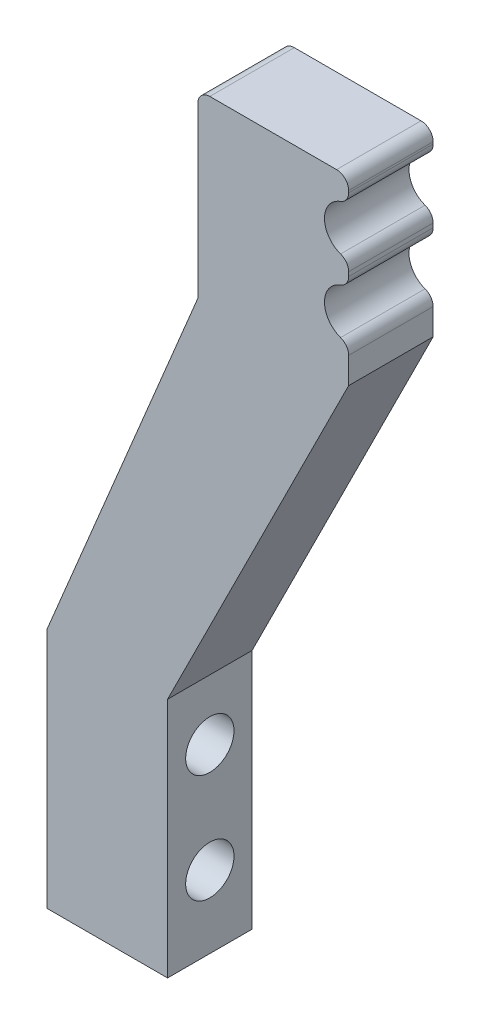
SolidWorks part; units mm, degrees
ref_plane "Front Plane" through (0, 0, 0) normal (0, 0, 1) x (1, 0, 0)
ref_plane "Top Plane" through (0, 0, 0) normal (0, 1, 0) x (1, 0, 0)
ref_plane "Right Plane" through (0, 0, 0) normal (1, 0, 0) x (0, 0, -1)
sketch "Sketch1" plane through (0, 0, 0) normal (0, 0, 1) x (1, 0, 0)
  line L1 (-137.2781, 244.3047) -> (-12.2781, 244.3047)
  line L3 (-262.2781, -205.6953) -> (-12.2781, -205.6953)
  line L4 (-12.2781, 244.3047) -> (-12.2781, -205.6953)
  line L5 (-137.2781, 244.3047) -> (-137.2781, 94.3047)
  line L6 (-137.2781, 94.3047) -> (-262.2781, -205.6953)
extrude "Boss-Extrude2" add sketch "Sketch1" along normal blind 70
sketch "Sketch2" plane through (0, 0, 70) normal (0, 0, 1) x (1, 0, 0)
  line L0 (-262.2781, -205.6953) -> (-262.2781, -405.6953)
  line L2 (-262.2781, -405.6953) -> (-162.2781, -405.6953)
  line L3 (-162.2781, -405.6953) -> (-162.2781, -205.6953)
  line L4 (-262.2781, -205.6953) -> (-12.2781, -205.6953) construction
  line L5 (-162.2781, -205.6953) -> (-262.2781, -205.6953)
extrude "Boss-Extrude3" add sketch "Sketch2" against normal blind 70
sketch "Sketch3" plane through (-162.2781, 0, 0) normal (1, 0, 0) x (0, 0, -1)
  circle A1 centre (-35, -255.6953) radius 20
  circle A2 centre (-35, -345.6953) radius 20
extrude "Cut-Extrude1" cut sketch "Sketch3" against normal blind 132
sketch "Sketch5" plane through (0, 0, 70) normal (0, 0, 1) x (1, 0, 0)
  line L0 (-12.2781, 94.3047) -> (-12.2781, -205.6953)
  line L1 (-12.2781, -205.6953) -> (-12.2781, 244.3047) construction
  line L2 (-162.2781, -205.6953) -> (-12.2781, 94.3047)
  line L3 (-12.2781, -205.6953) -> (-162.2781, -205.6953)
extrude "Cut-Extrude2" cut sketch "Sketch5" against normal blind 132
sketch "Sketch6" plane through (0, 0, 70) normal (0, 0, 1) x (1, 0, 0)
  line L2 (-12.2781, 224.3047) -> (-12.2781, 204.3047)
  line L6 (-12.2781, 204.3047) -> (-12.2781, 184.3047)
  line L9 (-12.2781, 144.3047) -> (-12.2781, 124.3047)
  line L10 (-12.2781, 94.3047) -> (-12.2781, 244.3047) construction
  line L11 (-12.2781, 164.3047) -> (-12.2781, 144.3047)
  arc A1 (-12.2781, 224.3047) -> (-12.2781, 184.3047) centre (-12.2781, 204.3047) ccw
  arc A2 (-12.2781, 164.3047) -> (-12.2781, 124.3047) centre (-12.2781, 144.3047) ccw
extrude "Cut-Extrude3" cut sketch "Sketch6" against normal blind 132
sketch "Sketch9" plane through (0, 0, 70) normal (0, 0, 1) x (1, 0, 0)
  line L0 (-127.2781, 244.3047) -> (-137.2781, 244.3047)
  line L1 (-137.2781, 244.3047) -> (-137.2781, 234.3047)
  arc A0 (-137.2781, 234.3047) -> (-127.2781, 244.3047) centre (-127.2781, 234.3047) cw
  point P8 (-137.2781, 244.3047)
extrude "Cut-Extrude4" cut sketch "Sketch9" against normal blind 79
sketch "Sketch11" plane through (0, 0, 70) normal (0, 0, 1) x (1, 0, 0)
  line L2 (-12.2781, 232.589) -> (-12.2781, 224.3047)
  line L3 (-12.2781, 224.3047) -> (-18.9448, 223.1609)
  arc A1 (-18.9448, 223.1609) -> (-12.2781, 232.589) centre (-22.2781, 232.589) ccw
  point P10 (-12.2781, 224.3047)
extrude "Cut-Extrude6" cut sketch "Sketch11" against normal blind 79
sketch "Sketch12" plane through (0, 0, 70) normal (0, 0, 1) x (1, 0, 0)
  line L0 (-18.9448, 125.4486) -> (-12.2781, 124.3047)
  line L2 (-18.9448, 185.4486) -> (-12.2781, 184.3047)
  line L3 (-12.2781, 184.3047) -> (-12.2781, 176.0205)
  line L4 (-18.9448, 163.1609) -> (-12.2781, 164.3047)
  line L5 (-12.2781, 164.3047) -> (-12.2781, 172.589)
  line L6 (-12.2781, 124.3047) -> (-12.2781, 116.0205)
  arc A2 (-12.2781, 176.0205) -> (-18.9448, 185.4486) centre (-22.2781, 176.0205) ccw
  arc A3 (-18.9448, 163.1609) -> (-12.2781, 172.589) centre (-22.2781, 172.589) ccw
  arc A4 (-12.2781, 116.0205) -> (-18.9448, 125.4486) centre (-22.2781, 116.0205) ccw
  point P15 (-12.2781, 184.3047)
  point P18 (-12.2781, 164.3047)
  point P21 (-12.2781, 124.3047)
extrude "Cut-Extrude7" cut sketch "Sketch12" against normal blind 79
sketch "Sketch13" plane through (0, 0, 70) normal (0, 0, 1) x (1, 0, 0)
  line L0 (-22.2781, 244.3047) -> (-12.2781, 244.3047)
  line L1 (-12.2781, 244.3047) -> (-12.2781, 234.3047)
  arc A0 (-12.2781, 234.3047) -> (-22.2781, 244.3047) centre (-22.2781, 234.3047) ccw
  point P8 (-12.2781, 244.3047)
extrude "Cut-Extrude8" cut sketch "Sketch13" against normal blind 79
